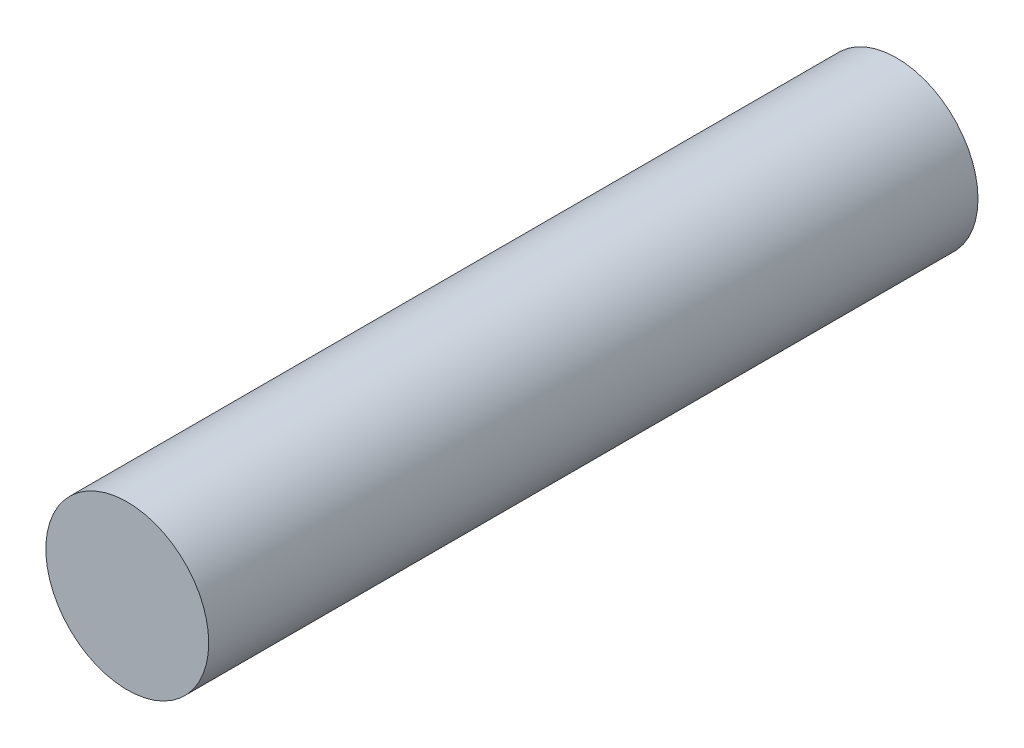
SolidWorks part; units mm, degrees
ref_plane "Alzado" through (0, 0, 0) normal (0, 0, 1) x (1, 0, 0)
ref_plane "Planta" through (0, 0, 0) normal (0, 1, 0) x (1, 0, 0)
ref_plane "Vista lateral" through (0, 0, 0) normal (1, 0, 0) x (0, 0, -1)
sketch "Croquis1" plane through (0, 0, 0) normal (0, 0, 1) x (1, 0, 0)
  circle A0 centre (0, 0) radius 7.94
  dimension "D1" = 15.88
extrude "Saliente-Extruir1" add sketch "Croquis1" along normal mid plane 75
